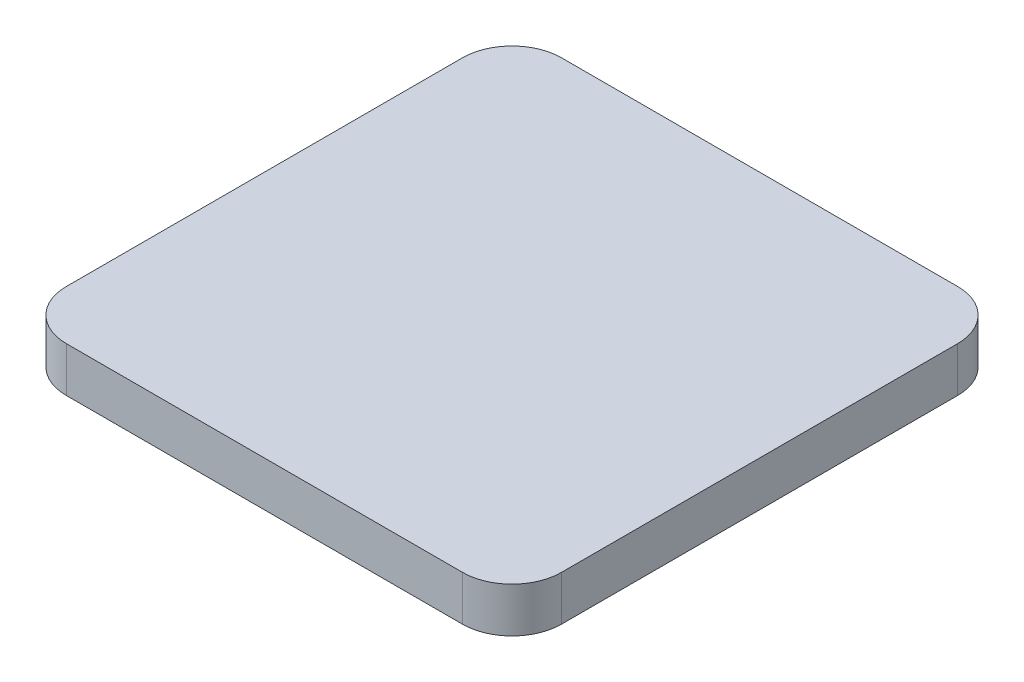
SolidWorks part; units mm, degrees
ref_plane "Front Plane" through (0, 0, 0) normal (0, 0, 1) x (1, 0, 0)
ref_plane "Top Plane" through (0, 0, 0) normal (0, 1, 0) x (1, 0, 0)
ref_plane "Right Plane" through (0, 0, 0) normal (1, 0, 0) x (0, 0, -1)
sketch "Sketch1" plane through (0, 0, 0) normal (0, 1, 0) x (1, 0, 0)
  line L1 (0, 0) -> (70, 0)
  line L2 (0, 0) -> (0, 70)
  line L3 (0, 70) -> (70, 70)
  line L4 (70, 0) -> (70, 70)
  dimension "D1" = 70
  dimension "D2" = 70
extrude "Boss-Extrude1" add sketch "Sketch1" along normal blind 6.35
fillet "Fillet1" radius 7 4 edges at (70, 3.175, -70) (70, 3.175, 0) (0, 3.175, 0) (0, 3.175, -70)
